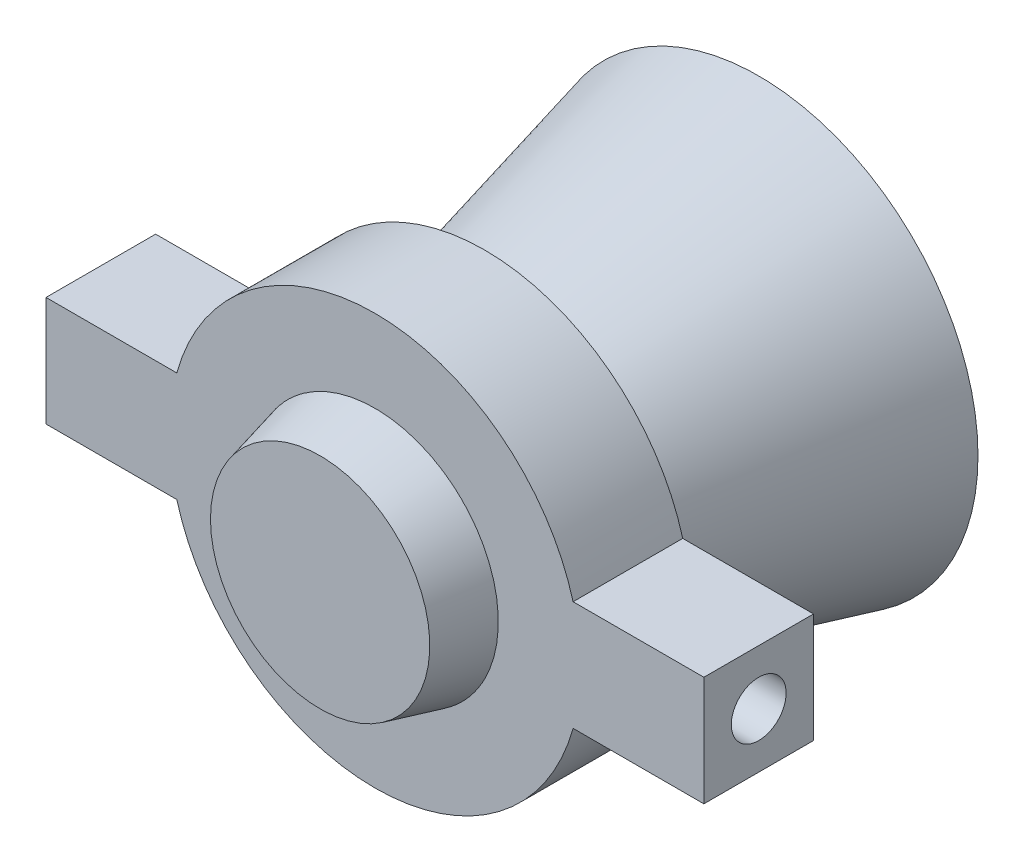
SolidWorks part; units mm, degrees
ref_plane "Front Plane" through (0, 0, 0) normal (1, 0, 0) x (0, 1, 0)
ref_plane "Top Plane" through (0, 0, 0) normal (0, 0, 1) x (0, 1, 0)
ref_plane "Right Plane" through (0, 0, 0) normal (0, 1, 0) x (-1, 0, 0)
sketch "Sketch1" plane through (0, 0, 0) normal (1, 0, 0) x (0, 1, 0)
  line L0 (0, 0) -> (0, 50.8) construction
  line L1 (0, 50.8) -> (-12.7, 50.8)
  line L2 (-12.7, 50.8) -> (-25.4, 0)
  line L3 (-25.4, 0) -> (0, 0)
  line L4 (0, 50.8) -> (0, 0)
  dimension "D1" = 25.4
  dimension "D2" = 50.8
  dimension "D3" = 50.8
revolve "Revolve1" add sketch "Sketch1" angle 360 about L0
sketch "Sketch4" plane through (0, 0, 0) normal (1, 0, 0) x (0, 1, 0)
  line L0 (-14.2875, 44.45) -> (-17.4625, 31.75)
  line L1 (-12.7, 50.8) -> (-25.4, 0) construction
  line L2 (-17.4625, 31.75) -> (-23.8125, 31.75)
  line L3 (-23.8125, 31.75) -> (-23.8125, 44.45)
  line L4 (-23.8125, 44.45) -> (-14.2875, 44.45)
  line L5 (12.7, 50.8) -> (-12.7, 50.8) construction
  line L6 (0, 0) -> (0, 23.0573) construction
  point P11 (0, 23.0573)
  dimension "D1" = 6.35
  dimension "D2" = 12.7
  dimension "D3" = 6.35
revolve "Revolve2" add sketch "Sketch4" angle 360 about L6
sketch "Sketch5" plane through (0, 0, 0) normal (1, 0, 0) x (0, 1, 0)
  line L0 (23.8125, 44.45) -> (-23.8125, 44.45) construction
  line L1 (-6.35, 44.45) -> (6.35, 44.45)
  line L2 (-6.35, 44.45) -> (-6.35, 31.75)
  line L3 (-6.35, 31.75) -> (6.35, 31.75)
  line L4 (6.35, 44.45) -> (6.35, 31.75)
  line L6 (-23.8125, 31.75) -> (23.8125, 31.75) construction
  point P4 (0, 31.75)
  point P8 (0, 0)
  point P9 (-6.0939, 32.2623)
extrude "Boss-Extrude2" add sketch "Sketch5" against normal up to surface (15.1498 mm away) from offset 38.1
sketch "Sketch7" plane through (38.1, 0, 0) normal (1, 0, 0) x (0, 1, 0)
  line L0 (-6.35, 31.75) -> (6.35, 44.45) construction
  circle A0 centre (0, 38.1) radius 3.175
  dimension "D1" = 6.35
extrude "Cut-Extrude3" cut sketch "Sketch7" against normal blind 19.05
mirror "Mirror3" about plane through (0, 0, 0) normal (1, 0, 0) of "Boss-Extrude2", "Cut-Extrude3"
